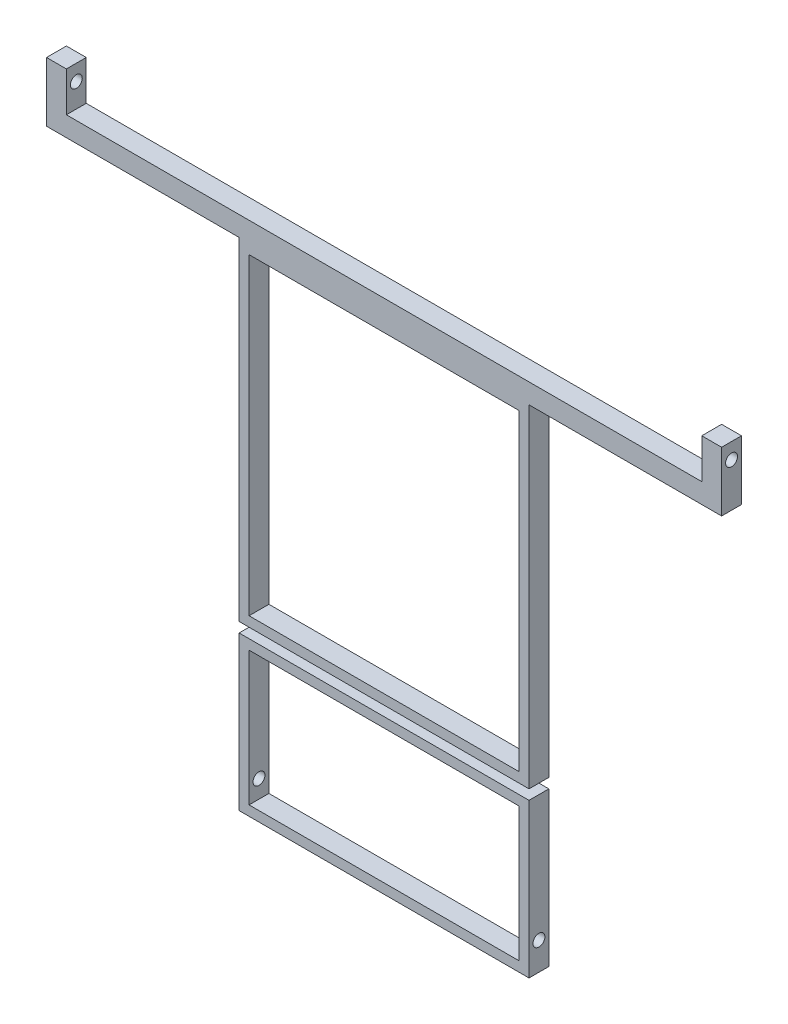
SolidWorks part; units mm, degrees
ref_plane "Front Plane" through (0, 0, 0) normal (0, 0, 1) x (1, 0, 0)
ref_plane "Top Plane" through (0, 0, 0) normal (0, 1, 0) x (1, 0, 0)
ref_plane "Right Plane" through (0, 0, 0) normal (1, 0, 0) x (0, 0, -1)
sketch "Sketch1" plane through (0, 0, 0) normal (0, 0, 1) x (1, 0, 0)
  line L0 (0, 0) -> (800, 0)
  line L1 (800, 0) -> (800, 50)
  line L2 (800, 50) -> (825, 50)
  line L3 (825, 50) -> (825, -25)
  line L4 (825, -25) -> (-25, -25)
  line L5 (-25, -25) -> (-25, 50)
  line L6 (-25, 50) -> (0, 50)
  line L7 (0, 50) -> (0, 0)
  dimension "D1" = 800
  dimension "D2" = 850
  dimension "D3" = 25
  dimension "D4" = 25
  dimension "D5" = 75
  dimension "D6" = 75
extrude "Boss-Extrude1" add sketch "Sketch1" along normal blind 25
sketch "Sketch2" plane through (825, 0, 0) normal (1, 0, 0) x (0, 0, -1)
  line L0 (0, -25) -> (0, 50) construction
  line L2 (-25, 50) -> (0, 50) construction
  circle A0 centre (-12.5, 30) radius 7.5
  dimension "D1" = 12.5
  dimension "D2" = 20
extrude "Cut-Extrude1" cut sketch "Sketch2" against normal blind 10000
sketch "Sketch3" plane through (0, -25, 0) normal (0, -1, 0) x (1, 0, 0)
  line L0 (-25, 25) -> (825, 25) construction
  line L1 (217.5, 25) -> (582.5, 25)
  line L2 (217.5, 25) -> (217.5, 0)
  line L3 (217.5, 0) -> (582.5, 0)
  line L4 (582.5, 25) -> (582.5, 0)
  line L5 (-25, 0) -> (825, 0) construction
  line L6 (-25, 25) -> (-25, 0) construction
  line L10 (825, 25) -> (825, 0) construction
  dimension "D1" = 365
  dimension "D2" = 242.5
  dimension "D3" = 242.5
extrude "Boss-Extrude3" add sketch "Sketch3" along normal blind 625
sketch "Sketch4" plane through (0, 0, 25) normal (0, 0, 1) x (1, 0, 0)
  line L0 (582.5, -650) -> (217.5, -650) construction
  line L1 (230, -637.5) -> (570, -637.5)
  line L2 (230, -637.5) -> (230, -37.5)
  line L3 (230, -37.5) -> (570, -37.5)
  line L4 (570, -637.5) -> (570, -37.5)
  line L5 (582.5, -650) -> (582.5, -25) construction
  line L6 (217.5, -650) -> (217.5, -25) construction
  line L7 (582.5, -25) -> (825, -25) construction
  dimension "D1" = 12.5
  dimension "D2" = 12.5
  dimension "D3" = 12.5
  dimension "D4" = 12.5
extrude "Cut-Extrude2" cut sketch "Sketch4" against normal blind 625
sketch "Sketch5" plane through (0, 0, 0) normal (0, 0, 1) x (1, 0, 0)
  line L0 (217.5, -650) -> (217.5, -25) construction
  line L1 (217.5, -431.2624) -> (582.5, -431.2624)
  line L2 (217.5, -431.2624) -> (217.5, -468.7624)
  line L3 (217.5, -468.7624) -> (582.5, -468.7624)
  line L4 (582.5, -431.2624) -> (582.5, -468.7624)
  line L5 (582.5, -650) -> (582.5, -25) construction
  dimension "D1" = 37.5
extrude "Boss-Extrude4" add sketch "Sketch5" along normal blind 25
sketch "Sketch6" plane through (0, 0, 25) normal (0, 0, 1) x (1, 0, 0)
  line L1 (197.0269, -456.2624) -> (603.1508, -456.2624)
  line L2 (197.0269, -456.2624) -> (197.0269, -443.7624)
  line L3 (197.0269, -443.7624) -> (603.1508, -443.7624)
  line L4 (603.1508, -456.2624) -> (603.1508, -443.7624)
  line L6 (570, -431.2624) -> (230, -431.2624) construction
  dimension "D1" = 12.5
  dimension "D2" = 12.5
extrude "Cut-Extrude3" cut sketch "Sketch6" against normal blind 25
sketch "Sketch7" plane through (217.5, 0, 0) normal (-1, 0, 0) x (0, 0, 1)
  line L0 (25, -650) -> (0, -650) construction
  line L3 (25, -650) -> (25, -456.2624) construction
  circle A0 centre (12.5, -615) radius 7.5
  point P6 (25, -617.1803)
  point P7 (25, -617.6302)
  dimension "D1" = 15
  dimension "D2" = 35
  dimension "D3" = 12.5
extrude "Cut-Extrude4" cut sketch "Sketch7" against normal through all both and the other way through all
